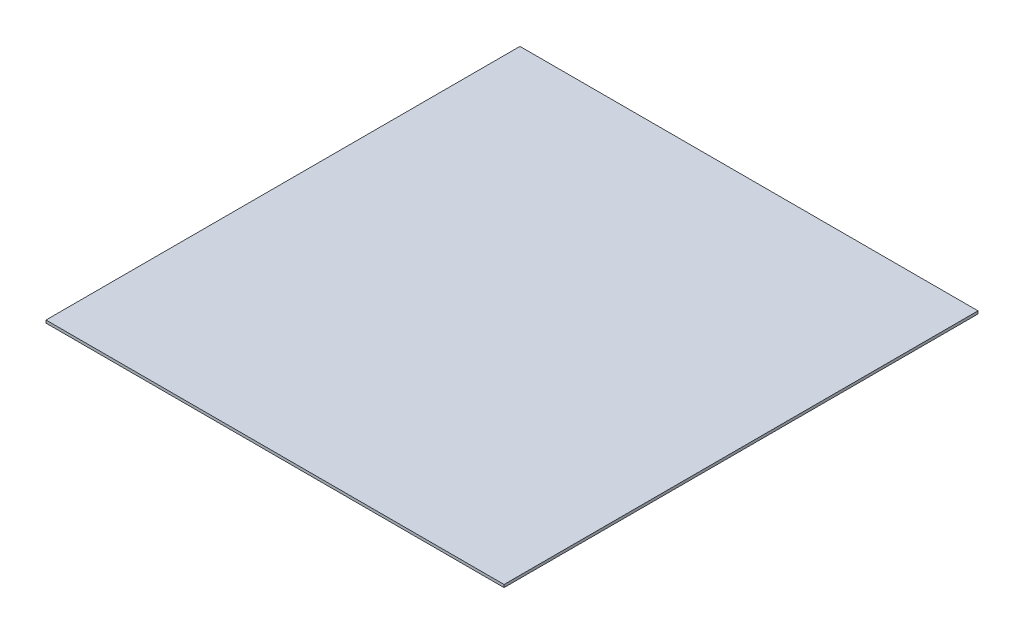
SolidWorks part; units mm, degrees
material "Cedar"
ref_plane "Front Plane" through (0, 0, 0) normal (0, 0, 1) x (1, 0, 0)
ref_plane "Top Plane" through (0, 0, 0) normal (0, 1, 0) x (1, 0, 0)
ref_plane "Right Plane" through (0, 0, 0) normal (1, 0, 0) x (0, 0, -1)
sketch "Sketch1" plane through (0, 0, 0) normal (0, 1, 0) x (1, 0, 0)
  line L1 (0, 0) -> (1500, 0)
  line L2 (0, 0) -> (0, -1552)
  line L3 (0, -1552) -> (1500, -1552)
  line L4 (1500, 0) -> (1500, -1552)
  dimension "D1" = 1500
  dimension "D2" = 1552
extrude "Boss-Extrude1" add sketch "Sketch1" along normal blind 9
